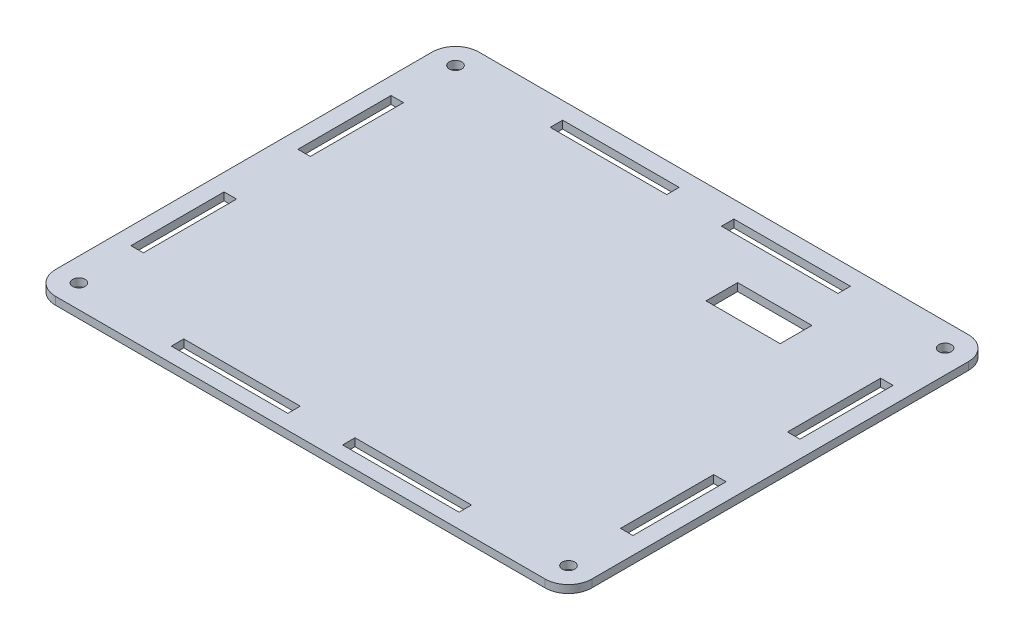
SolidWorks part; units mm, degrees
ref_plane "Front Plane" through (0, 0, 0) normal (0, 0, 1) x (1, 0, 0)
ref_plane "Top Plane" through (0, 0, 0) normal (0, 1, 0) x (1, 0, 0)
ref_plane "Right Plane" through (0, 0, 0) normal (1, 0, 0) x (0, 0, -1)
sketch "Sketch1" plane through (0, 0, 0) normal (0, 1, 0) x (1, 0, 0)
  line L0 (0, 8.1414) -> (0, -124047.6473) construction
  line L1 (0, 0) -> (138.1, 0)
  line L2 (0, 0) -> (0, 109)
  line L3 (0, 109) -> (138.1, 109)
  line L4 (138.1, 0) -> (138.1, 109)
  line L9 (3.753, 0) -> (124059.5417, 0) construction
  line L10 (12, 0) -> (12, -50000) construction
  line L11 (126.1, 0) -> (126.1, -50000) construction
  line L12 (0, 12) -> (-50000, 12) construction
  line L13 (-45.6158, 97) -> (49954.3842, 97) construction
  line L14 (-2.2542, 48) -> (-50002.2542, 48) construction
  line L15 (-71.6312, 38) -> (49928.3688, 38) construction
  line L16 (82.1, 114.3993) -> (82.1, -49885.6007) construction
  line L17 (60, 108.3918) -> (60, -49891.6082) construction
  line L18 (92.1, 117.8875) -> (92.1, -49882.1125) construction
  line L19 (32, 7.0141) -> (62, 7.0141)
  line L20 (32, 104.6) -> (62, 104.6)
  line L21 (32, 104.6) -> (32, 101.4)
  line L22 (32, 101.4) -> (62, 101.4)
  line L23 (62, 104.6) -> (62, 101.4)
  line L24 (106.1, 104.6) -> (76.1, 104.6)
  line L25 (106.1, 104.6) -> (106.1, 101.4)
  line L26 (106.1, 101.4) -> (76.1, 101.4)
  line L27 (76.1, 104.6) -> (76.1, 101.4)
  line L28 (32, 7.0141) -> (32, 3.8141)
  line L29 (32, 3.8141) -> (62, 3.8141)
  line L30 (62, 7.0141) -> (62, 3.8141)
  line L31 (106.1, 7.0141) -> (76.1, 7.0141)
  line L32 (106.1, 7.0141) -> (106.1, 3.8141)
  line L33 (106.1, 3.8141) -> (76.1, 3.8141)
  line L34 (76.1, 7.0141) -> (76.1, 3.8141)
  line L40 (4.4, 88) -> (7.6, 88)
  line L41 (4.4, 88) -> (4.4, 64)
  line L42 (4.4, 64) -> (7.6, 64)
  line L43 (7.6, 88) -> (7.6, 64)
  line L44 (4.4, 45) -> (7.6, 45)
  line L45 (4.4, 45) -> (4.4, 21)
  line L46 (4.4, 21) -> (7.6, 21)
  line L47 (7.6, 45) -> (7.6, 21)
  line L48 (130.5, 88) -> (133.7, 88)
  line L49 (130.5, 88) -> (130.5, 64)
  line L50 (130.5, 64) -> (133.7, 64)
  line L51 (133.7, 88) -> (133.7, 64)
  line L52 (130.5, 45) -> (133.7, 45)
  line L53 (130.5, 45) -> (130.5, 21)
  line L54 (130.5, 21) -> (133.7, 21)
  line L55 (133.7, 45) -> (133.7, 21)
  line L56 (109.87, 90.904) -> (90.769, 90.904)
  line L57 (109.87, 90.904) -> (109.87, 82.751)
  line L58 (109.87, 82.751) -> (90.769, 82.751)
  line L59 (90.769, 90.904) -> (90.769, 82.751)
  circle A7 centre (6, 103) radius 1.6
  circle A8 centre (132.1, 103) radius 1.6
  circle A9 centre (132.1, 6) radius 1.6
  circle A10 centre (6, 6) radius 1.6
  point P76 (132.1, 21)
  point P77 (132.1, 64)
  point P78 (32, 103)
  dimension "D14" = 8.153
  dimension "D22" = 6
  dimension "D24" = 6
  dimension "D26" = 6
  dimension "D28" = 6
  dimension "D1" = 109
  dimension "D2" = 138.1
  dimension "D3" = 12
  dimension "D4" = 12
  dimension "D6" = 12
  dimension "D7" = 49
  dimension "D8" = 10
  dimension "D9" = 26
  dimension "D10" = 70.1
  dimension "D11" = 48
  dimension "D12" = 10
  dimension "D13" = 34
  dimension "D15" = 19.101
  dimension "D23" = 6
  dimension "D25" = 6
  dimension "D27" = 6
  dimension "D29" = 6
  dimension "D30" = 30
  dimension "D31" = 20
  dimension "D32" = 3.2
  dimension "D33" = 30
  dimension "D34" = 20
  dimension "D35" = 20
  dimension "D36" = 3.2
  dimension "D37" = 20
  dimension "D38" = 30
  dimension "D39" = 30
  dimension "D40" = 24
  dimension "D41" = 9
  dimension "D42" = 19
  dimension "D43" = 24
  dimension "D44" = 24
  dimension "D45" = 24
  dimension "D46" = 9
  dimension "D47" = 19
  dimension "D48" = 3.2
  dimension "D49" = 1.6
  dimension "D50" = 3.2
  dimension "D51" = 3.2
  dimension "D52" = 14.1
  dimension "D53" = 14.1
extrude "Boss-Extrude1" add sketch "Sketch1" along normal blind 2
fillet "Fillet1" radius 6 1 edges at (0, 1, -109)
fillet "Fillet2" radius 6 1 edges at (0, 1, 0)
fillet "Fillet3" radius 6 2 edges at (138.1, 1, -109) (138.1, 1, 0)
